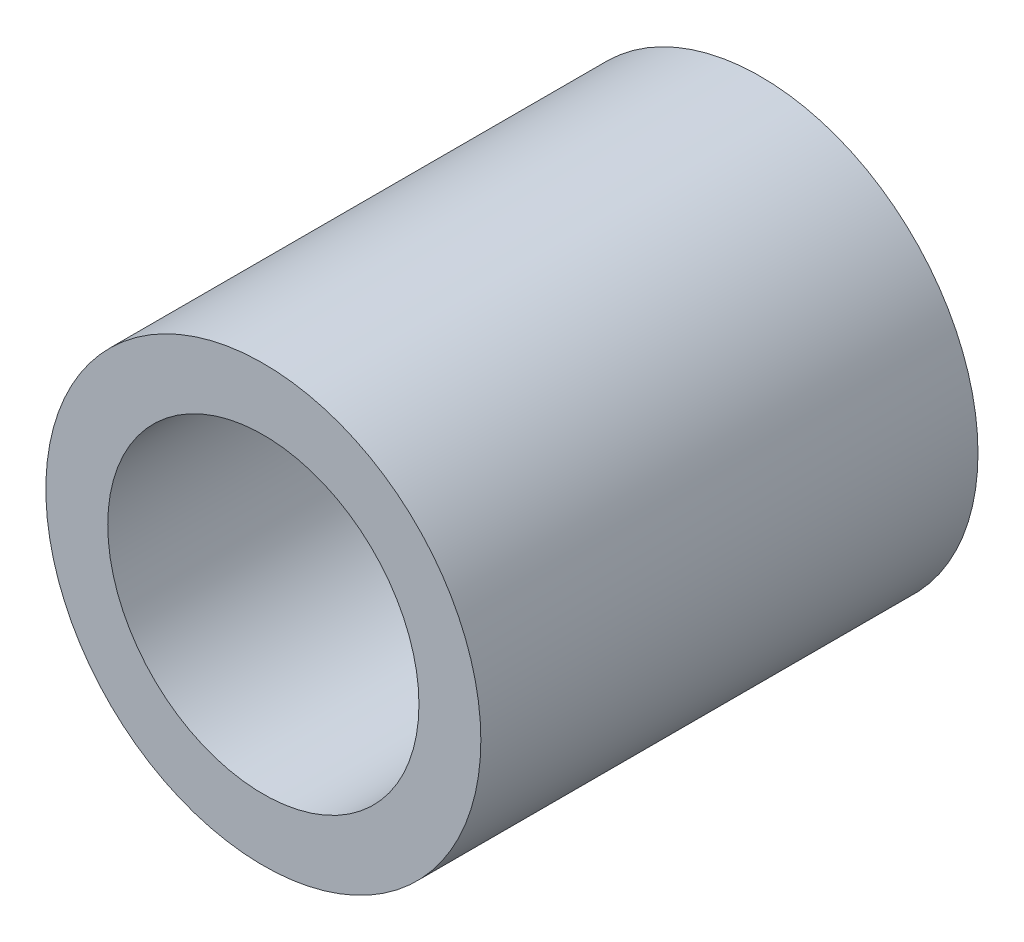
SolidWorks part; units mm, degrees
ref_plane "Front Plane" through (0, 0, 0) normal (0, 0, 1) x (1, 0, 0)
ref_plane "Top Plane" through (0, 0, 0) normal (0, 1, 0) x (1, 0, 0)
ref_plane "Right Plane" through (0, 0, 0) normal (1, 0, 0) x (0, 0, -1)
sketch "Sketch1" plane through (0, 0, 0) normal (0, 0, 1) x (1, 0, 0)
  circle A0 centre (0, 0) radius 5.5562
  circle A1 centre (0, 0) radius 3.9751
  dimension "D1" = 11.1125
  dimension "ID" = 7.9502
extrude "Extrude1" add sketch "Sketch1" along normal mid plane 12.7
sketch "Sketch2" plane through (0, 0, 0) normal (1, 0, 0) x (0, 0, -1)
  line L0 (-6.35, -3.9751) -> (6.35, -3.9751) construction
  line L3 (6.35, 3.9751) -> (-6.35, 3.9751) construction
  line L5 (-6.35, -3.9751) -> (6.35, -3.9751)
  line L6 (6.35, 3.9751) -> (-6.35, 3.9751)
sketch "Sketch4" plane through (0, 0, 6.35) normal (0, 0, 1) x (1, 0, 0)
  line L0 (0, 0) -> (-2.8108, 2.8108)
  line L1 (0, -48.895) -> (0, 48.895) construction
  circle A0 centre (0, 0) radius 3.9751 construction
  dimension "D1" = 45
